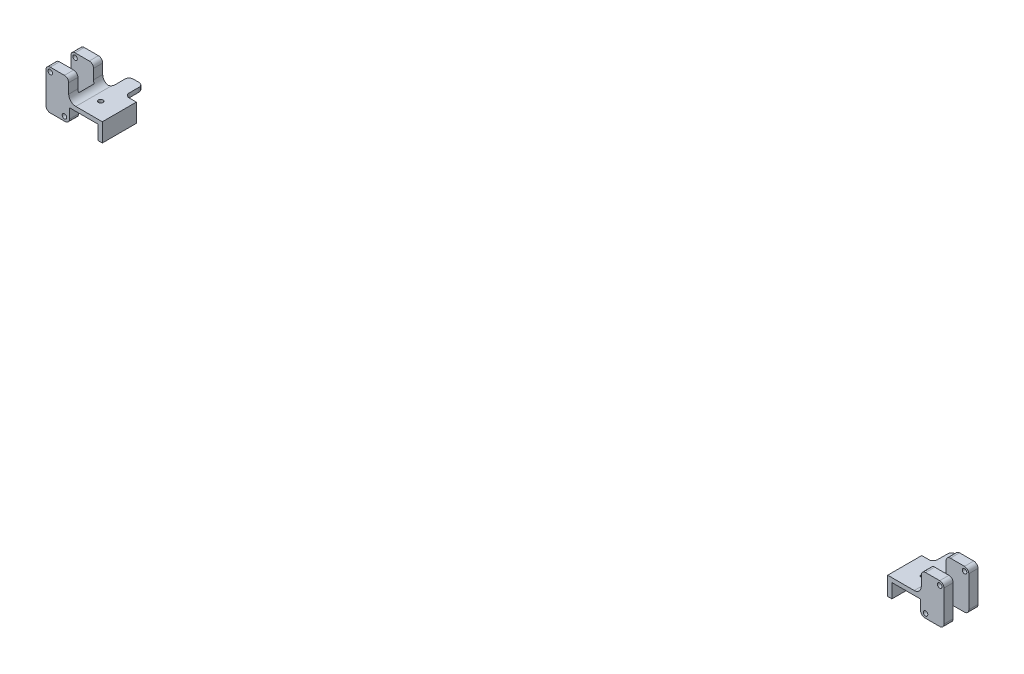
SolidWorks part; units mm, degrees
material "光敏树脂"
ref_plane "前视基准面" through (0, 0, 0) normal (0, 0, 1) x (1, 0, 0)
ref_plane "上视基准面" through (0, 0, 0) normal (0, 1, 0) x (1, 0, 0)
ref_plane "右视基准面" through (0, 0, 0) normal (1, 0, 0) x (0, 0, -1)
sketch "草图1" plane through (0, 0, 0) normal (0, 0, 1) x (1, 0, 0)
  line L0 (0, 96.72) -> (0, -75.892) construction
  line L1 (-70.2945, 0) -> (72.6376, 0) construction
  line L2 (-10.1, 0) -> (-10.1, 10)
  line L3 (-10.1, 10) -> (10.1, 10)
  line L4 (10.1, 10) -> (10.1, 0)
  line L5 (-13.1, 0) -> (-13.1, 13)
  line L6 (-13.1, 13) -> (10.6, 13)
  line L8 (-13.1, 0) -> (-10.1, 0)
  line L9 (10.1, 0) -> (13.1, 0)
  line L11 (13.1, 0) -> (26.6, 0)
  line L12 (13.1, 13) -> (13.1, 0) construction
  line L13 (26.6, 0) -> (26.6, 28)
  line L14 (26.6, 28) -> (10.6, 28)
  line L15 (10.6, 28) -> (10.6, 13)
  line L17 (-13.1, 13) -> (13.1, 13) construction
  circle A0 centre (23.6, 25) radius 1.6
  circle A1 centre (13.6, 3) radius 1.6
  point P14 (0, 10)
  dimension "D4" = 3.2
  dimension "D1" = 3
  dimension "D2" = 20.2
  dimension "D3" = 13
  dimension "D5" = 10
  dimension "D6" = 22
  dimension "D7" = 3.5
  dimension "D8" = 3
  dimension "D9" = 3
  dimension "D10" = 3
  dimension "D11" = 16
extrude "凸台-拉伸1" add sketch "草图1" along normal mid plane 24
sketch "草图2" plane through (0, 0, 0) normal (0, -1, 0) x (1, 0, 0)
  line L0 (-1.6961, 0) -> (30.7712, 0) construction
  line L1 (18.35, 12) -> (18.35, -12) construction
  line L2 (10.1, 12) -> (26.6, 12) construction
  line L3 (10.1, -12) -> (26.6, -12) construction
  line L4 (26.6, 12) -> (26.6, -12) construction
  line L5 (10.1, 5.5) -> (26.6, 5.5)
  line L6 (10.1, 5.5) -> (10.1, -5.5)
  line L7 (10.1, -5.5) -> (26.6, -5.5)
  line L8 (26.6, 5.5) -> (26.6, -5.5)
  line L9 (10.1, 5.5) -> (26.6, -5.5) construction
  line L10 (10.1, -5.5) -> (26.6, 5.5) construction
  point P9 (18.35, 0)
  dimension "D1" = 11
extrude "切除-拉伸1" cut sketch "草图2" against normal through all
sketch "草图3" plane through (0, 13, 0) normal (0, 1, 0) x (1, 0, 0)
  line L0 (0, 34.5076) -> (0, -20.8518) construction
  line L1 (10.6, 12) -> (-13.1, 12) construction
  line L2 (-5, 25) -> (5, 25)
  line L3 (-5, 25) -> (-5, 12)
  line L4 (-5, 12) -> (5, 12)
  line L5 (5, 25) -> (5, 12)
  line L6 (-5, 25) -> (5, 12) construction
  line L7 (-5, 12) -> (5, 25) construction
  line L8 (-20.2278, 0) -> (26.7988, 0) construction
  point P3 (0, 18.5)
  dimension "D1" = 25
  dimension "D2" = 10
extrude "凸台-拉伸2" add sketch "草图3" against normal up to surface (3 mm away) up to face at (3.3667, 10, 0)
sketch "草图4" plane through (0, 13, 0) normal (0, 1, 0) x (1, 0, 0)
  circle A0 centre (0, 0) radius 1.6
  dimension "D1" = 3.2
extrude "切除-拉伸2" cut sketch "草图4" against normal through all
fillet "圆角1" radius 3 12 edges at (-5, 11.5, -12) (5, 11.5, -12) (5, 11.5, -25) (-5, 11.5, -25) (10.1, 0, -8.75) (10.6, 28, -8.75) (26.6, 0, -8.75) (26.6, 28, -8.75) (10.6, 28, 8.75) (26.6, 28, 8.75) (26.6, 0, 8.75) (10.1, 0, 8.75)
fillet "圆角2" radius 5 1 edges at (10.6, 13, -8.75)
ref_plane "基准面1" through (-290, 0, 0) normal (1, 0, 0) x (0, 0, -1)
mirror "镜向1" about plane through (-290, 0, 0) normal (1, 0, 0) of bodies 109
